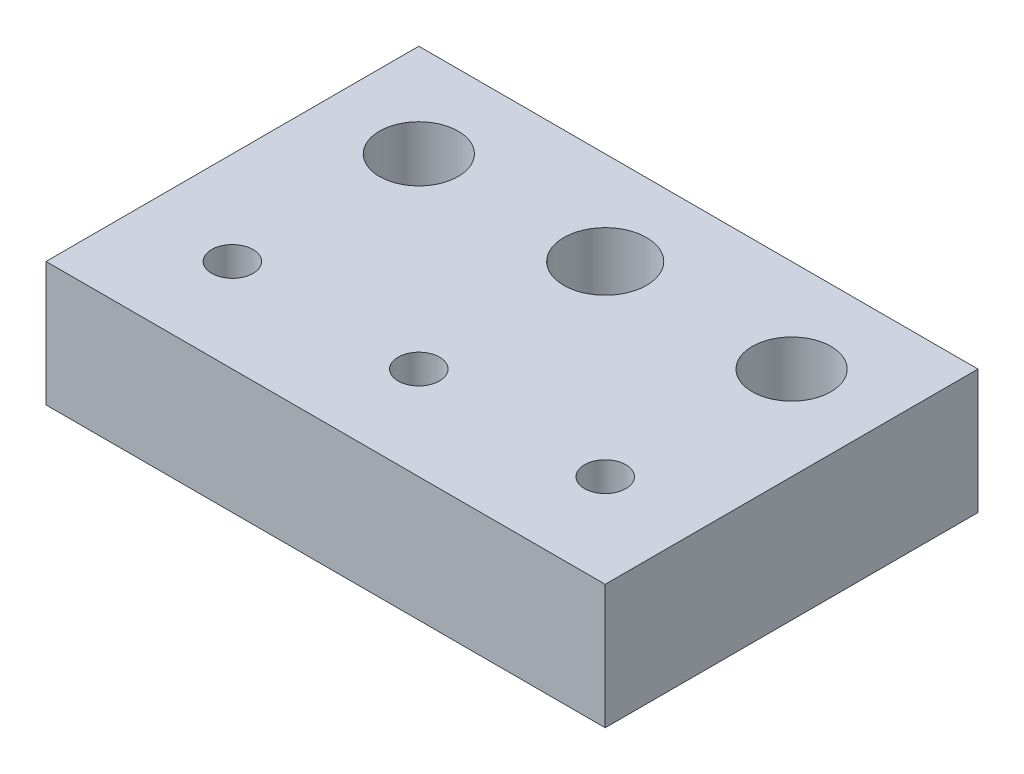
SolidWorks part; units mm, degrees
ref_plane "Front Plane" through (0, 0, 0) normal (0, 0, 1) x (1, 0, 0)
ref_plane "Top Plane" through (0, 0, 0) normal (0, 1, 0) x (1, 0, 0)
ref_plane "Right Plane" through (0, 0, 0) normal (1, 0, 0) x (0, 0, -1)
sketch "Sketch1" plane through (0, 0, 0) normal (0, 1, 0) x (1, 0, 0)
  line L9 (-67.5, -45) -> (67.5, -45)
  line L10 (-67.5, -45) -> (-67.5, 45)
  line L11 (-67.5, 45) -> (67.5, 45)
  line L12 (67.5, -45) -> (67.5, 45)
  line L13 (-67.5, -45) -> (67.5, 45) construction
  line L14 (-67.5, 45) -> (67.5, -45) construction
  line L16 (-67.5, 45) -> (-67.5, 22.5)
  circle A3 centre (-45, -22.5) radius 5
  circle A4 centre (45, -22.5) radius 5
  circle A5 centre (0, -22.5) radius 5
  circle A6 centre (0, 22.5) radius 10
  point P0 (0, 0)
  point P13 (0, 0)
  point P18 (0, 0)
extrude "Boss-Extrude2" add sketch "Sketch1" along normal blind 30 contours L9 L12 L11 L10 A6 A5 A3 A4
sketch "Sketch2" plane through (0, 30, 0) normal (0, 1, 0) x (1, 0, 0)
  circle A2 centre (-45, 22.5) radius 9.5
  circle A3 centre (45, 22.5) radius 9.5
extrude "Cut-Extrude2" cut sketch "Sketch2" against normal blind 20 contours A2 | A3
sketch "Sketch3" plane through (0, 0, 0) normal (0, -1, 0) x (1, 0, 0)
  circle A0 centre (45, 22.5) radius 8
  circle A1 centre (0, 22.5) radius 8
  circle A2 centre (-45, 22.5) radius 8
  point P8 (0, 0)
extrude "Cut-Extrude3" cut sketch "Sketch3" against normal blind 10
